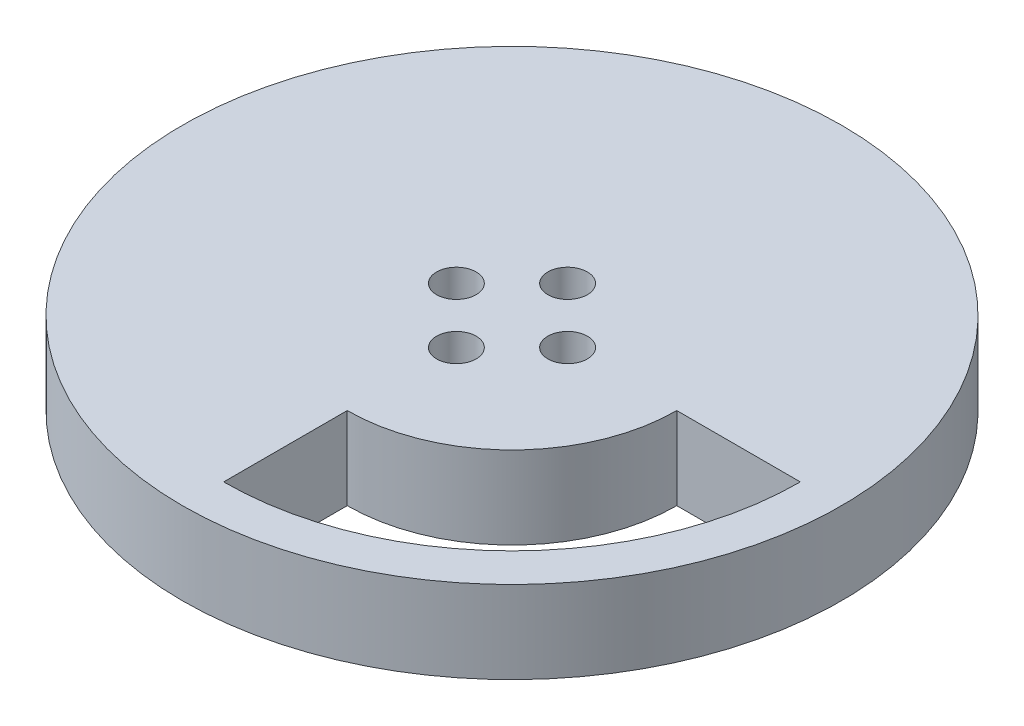
SolidWorks part; units mm, degrees
ref_plane "前视基准面" through (0, 0, 0) normal (0, 0, 1) x (1, 0, 0)
ref_plane "上视基准面" through (0, 0, 0) normal (0, 1, 0) x (1, 0, 0)
ref_plane "右视基准面" through (0, 0, 0) normal (1, 0, 0) x (0, 0, -1)
sketch "草图1" plane through (0, 0, 0) normal (0, 1, 0) x (1, 0, 0)
  line L0 (0, 12.9094) -> (0, -12.6269) construction
  line L1 (-12.2876, 0) -> (12.594, 0) construction
  circle A0 centre (0, 0) radius 40
  circle A1 centre (6.75, 0) radius 1.25
  circle A2 centre (0, -6.75) radius 1.25
  circle A3 centre (-6.75, 0) radius 1.25
  circle A4 centre (0, 6.75) radius 1.25
  point P18 (0, 0)
extrude "凸台-拉伸1" add sketch "草图1" along normal blind 10
sketch "草图2" plane through (0, 10, 0) normal (0, 1, 0) x (1, 0, 0)
  circle A0 centre (0, 6.75) radius 2.4
  circle A1 centre (6.75, 0) radius 2.4
  circle A2 centre (0, -6.75) radius 2.4
  circle A3 centre (-6.75, 0) radius 2.4
  point P12 (0, 0)
  dimension "D1" = 4
extrude "切除-拉伸1" cut sketch "草图2" against normal blind 6
sketch "草图3" plane through (0, 10, 0) normal (0, 1, 0) x (1, 0, 0)
  line L0 (20, 0) -> (35, 0)
  line L1 (0, -20) -> (0, -35)
  arc A0 (0, -20) -> (20, 0) centre (0, 0) ccw
  arc A1 (0, -35) -> (35, 0) centre (0, 0) ccw
  point P1 (0, 0)
extrude "切除-拉伸2" cut sketch "草图3" against normal through all
